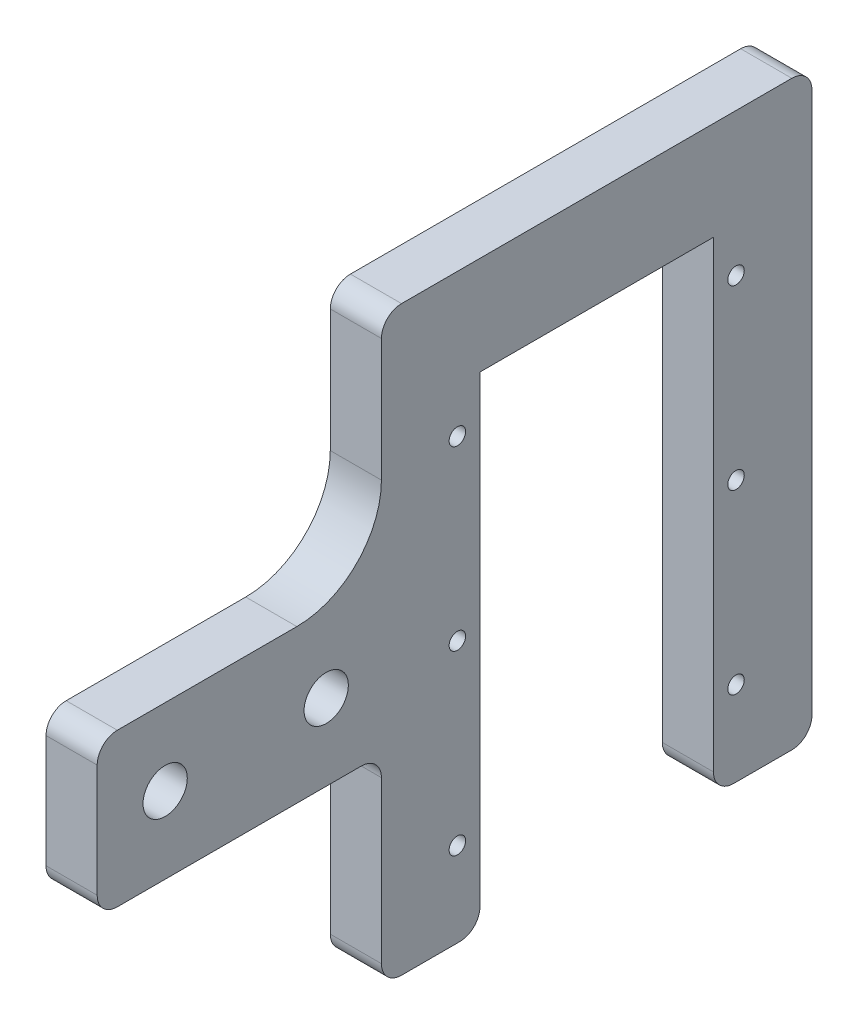
SolidWorks part; units mm, degrees
ref_plane "Front Plane" through (0, 0, 0) normal (0, 0, 1) x (1, 0, 0)
ref_plane "Top Plane" through (0, 0, 0) normal (0, 1, 0) x (1, 0, 0)
ref_plane "Right Plane" through (0, 0, 0) normal (1, 0, 0) x (0, 0, -1)
sketch "Sketch11" plane through (0, 0, 0) normal (1, 0, 0) x (0, 0, -1)
  line L0 (-62.0272, -19) -> (-62.0272, -12) construction
  line L1 (-62.0272, -25) -> (-62.0272, -6)
  line L2 (-62.0272, -25) -> (-25.1472, -25)
  line L3 (-25.1472, -25) -> (-25.1472, -6)
  line L4 (-62.0272, -6) -> (-25.1472, -6)
  line L6 (-515, -6) -> (-15, -6) construction
  line L7 (-25.1472, -12) -> (-25.1472, -19) construction
  point P6 (-62.0272, -15.5)
extrude "Boss-Extrude3" add sketch "Sketch11" along normal mid plane 6.35 separate body
sketch "Sketch8" plane through (0, 0, 0) normal (1, 0, 0) x (0, 0, -1)
  line L0 (0, 10) -> (0, 22.2316) construction
  line L1 (0, 5.5716) -> (0, -5.5716) construction
  line L16 (14.5, 10) -> (14.5, -50)
  line L17 (14.5, -50) -> (26.7316, -50)
  line L18 (26.7316, -50) -> (26.7316, 22.2316)
  line L19 (26.7316, 22.2316) -> (-26.7316, 22.2316)
  line L20 (-26.7316, 22.2316) -> (-26.7316, -50)
  line L21 (-26.7316, -50) -> (-14.5, -50)
  line L22 (-14.5, -50) -> (-14.5, 10)
  line L23 (-14.5, 10) -> (14.5, 10)
  dimension "D2" = 29
  dimension "D4" = 60
extrude "Boss-Extrude2" add sketch "Sketch8" along normal mid plane 6.35
sketch "Sketch4" plane through (-3.175, 0, 0) normal (-1, 0, 0) x (0, 0, 1)
  line L0 (14.5, -50) -> (14.5, 10) construction
  line L3 (0, 0.0539) -> (0, 22.3365) construction
  line L7 (26.7316, -50) -> (14.5, -50) construction
  line L8 (17.3, -39.5) -> (17.3, -17.5) construction
  line L9 (17.3, -17.5) -> (17.3, 4.5) construction
  circle A0 centre (17.3, -39.5) radius 1.025
  circle A1 centre (-17.3, -39.5) radius 1.025
  circle A2 centre (17.3, -17.5) radius 1.025
  circle A3 centre (-17.3, -17.5) radius 1.025
  circle A4 centre (-17.3, 4.5) radius 1.025
  circle A5 centre (17.3, 4.5) radius 1.025
  point P8 (0, 5.9386)
  dimension "D5" = 2.05
  dimension "D1" = 2.8
  dimension "D2" = 10.5
  dimension "D6" = 22
extrude "Cut-Extrude4" cut sketch "Sketch4" against normal through all
hole_wizard "M5 Clearance Hole1" positions "Sketch10" profile "Sketch9" hole size "M5" standard "ANSI Metric" end condition up to next
sketch "Sketch10" plane through (3.175, 0, 0) normal (1, 0, 0) x (0, 0, -1)
  circle A0 centre (-53.5872, -15.5) radius 2.1 construction
  circle A1 centre (-33.5872, -15.5) radius 2.1 construction
  point P0 (-53.5872, -15.5)
  point P5 (-33.5872, -15.5)
sketch "Sketch9" plane through (3.175, -15.5, 53.5872) normal (0, 1, 0) x (0, 0, -1)
  line L0 (0, 0) -> (0, 6.35)
  line L1 (0, 6.35) -> (2.75, 6.35)
  line L2 (2.75, 6.35) -> (2.75, 0)
  line L5 (2.75, 0) -> (0, 0)
  line L11 (0, -6.35) -> (0, 107.95) construction
  dimension "Thru Hole Dia." = 5.5
  dimension "Thru Hole Depth" = 6.35
fillet "Fillet1" radius 2.5 9 edges at (0, -50, -26.7316) (0, -50, -14.5) (0, -50, 14.5) (0, -50, 26.7316) (0, -25, 26.7316) (0, -25, 62.0272) (0, -6, 62.0272) (0, 22.2316, -26.7316) (0, 22.2316, 26.7316)
fillet "Fillet2" radius 10.5 1 edges at (0, -6, 26.7316)
